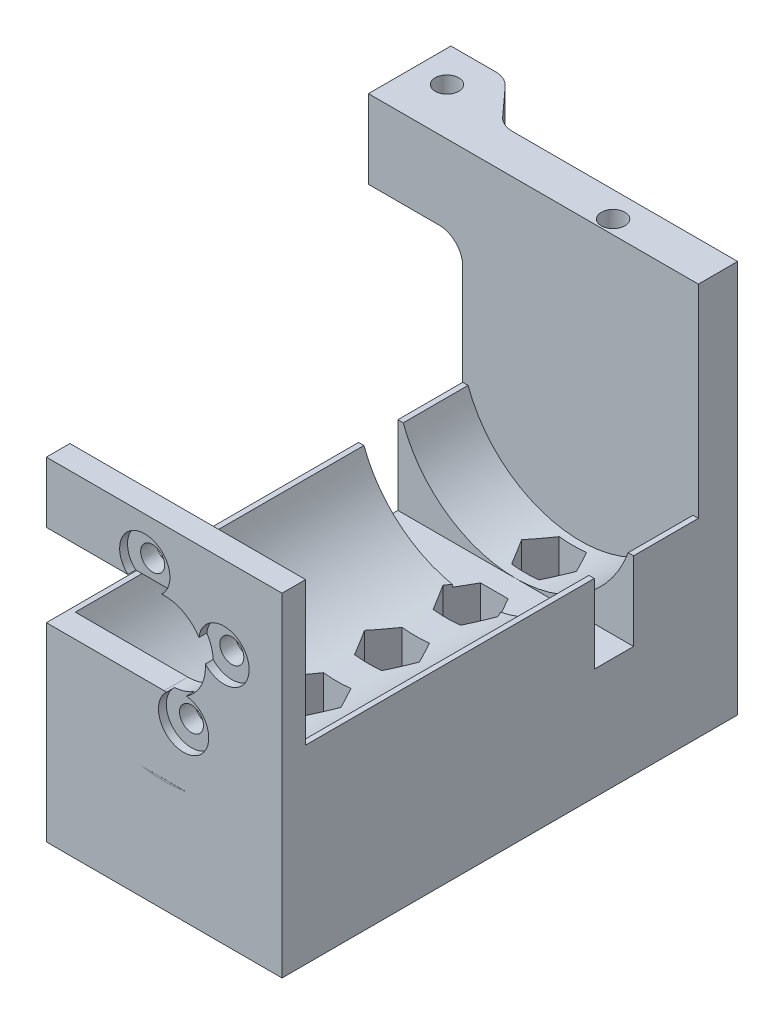
SolidWorks part; units mm, degrees
ref_plane "Front Plane" through (0, 0, 0) normal (0, 0, 1) x (1, 0, 0)
ref_plane "Top Plane" through (0, 0, 0) normal (0, 1, 0) x (1, 0, 0)
ref_plane "Right Plane" through (0, 0, 0) normal (1, 0, 0) x (0, 0, -1)
sketch "Sketch1" plane through (0, 0, 0) normal (0, 0, 1) x (1, 0, 0)
  line L1 (-15, -15) -> (15, -15)
  line L5 (-15, -15) -> (-15, -5.25)
  line L6 (15, -15) -> (15, 13)
  line L9 (-15, 13) -> (15, 13)
  line L11 (0, -5.25) -> (-15, -5.25)
  line L12 (0, 5.25) -> (-15, 5.25)
  line L13 (-15, 5.25) -> (-15, 13)
  line L14 (0, 0) -> (0, 8) construction
  line L15 (2.4721, -7.6085) -> (-2.4721, 7.6085) construction
  line L16 (0, 0) -> (7.6085, 2.4721) construction
  arc A0 (0, -5.25) -> (5.25, 0) centre (0, 0) ccw
  circle A1 centre (0, 0) radius 8 construction
  arc A5 (0, 5.25) -> (5.25, 0) centre (0, 0) cw
  circle A7 centre (-2.4721, 7.6085) radius 1.525
  circle A10 centre (7.6085, 2.4721) radius 1.525
  circle A11 centre (2.4721, -7.6085) radius 1.525
  dimension "D2" = 10.5
  dimension "D5" = 16
  dimension "D6" = 18
  dimension "D8" = 3.05
  dimension "D1" = 30
  dimension "D3" = 28
  dimension "D7" = 90
extrude "Boss-Extrude1" add sketch "Sketch1" along normal blind 3
sketch "Sketch2" plane through (0, 0, 3) normal (0, 0, 1) x (1, 0, 0)
  line L0 (-15, -15) -> (-15, -5.25)
  line L2 (-15, -15) -> (-15, -29.425)
  line L3 (-15, -29.425) -> (15, -29.425)
  line L4 (15, -15) -> (15, -29.425)
  line L6 (15, -15) -> (15, -5.25)
  line L8 (-15, -5.25) -> (-14.3178, -5.25)
  line L9 (0, -5.25) -> (-15, -5.25) construction
  line L10 (-14.3178, -5.25) -> (16.0436, -5.25) construction
  line L11 (15, -5.25) -> (14.3178, -5.25)
  arc A0 (-14.3178, -5.25) -> (14.3178, -5.25) centre (0, 0) ccw
  dimension "D2" = 30.5
  dimension "D4" = 15.25
  dimension "D1" = 14.425
  dimension "D3" = 14.425
extrude "Boss-Extrude2" add sketch "Sketch2" against normal blind 53
sketch "Sketch3" plane through (0, -29.425, 0) normal (0, -1, 0) x (-1, 0, 0)
  line L0 (0, -3) -> (0, 50) construction
  line L1 (15, -3) -> (-15, -3) construction
  line L2 (15, 50) -> (-15, 50) construction
  circle A0 centre (0, 46) radius 1.55
  circle A1 centre (0, 36) radius 1.55
  circle A2 centre (0, 26) radius 1.55
  circle A3 centre (0, 16) radius 1.55
  circle A4 centre (0, 6) radius 1.55
  dimension "D1" = 3.1
  dimension "D2" = 4
  dimension "D3" = 5
extrude "Cut-Extrude1" cut sketch "Sketch3" against normal through all
sketch "Sketch4" plane through (0, 0, 3) normal (0, 0, 1) x (1, 0, 0)
  line L0 (-2.75, -15) -> (2.694, -15.0102)
  arc A0 (-2.75, -15) -> (2.694, -15.0102) centre (0, 0) ccw
extrude "Boss-Extrude3" add sketch "Sketch4" against normal blind 3 separate body
sketch "Sketch5" plane through (0, -29.425, 0) normal (0, -1, 0) x (-1, 0, 0)
  line L0 (3.493, 36) -> (1.7465, 39.025)
  line L1 (3.493, 46) -> (1.7465, 49.025)
  line L2 (1.7465, 49.025) -> (-1.7465, 49.025)
  line L3 (-1.7465, 49.025) -> (-3.493, 46)
  line L4 (-3.493, 46) -> (-1.7465, 42.975)
  line L5 (-1.7465, 42.975) -> (1.7465, 42.975)
  line L6 (1.7465, 42.975) -> (3.493, 46)
  line L7 (1.7465, 39.025) -> (-1.7465, 39.025)
  line L8 (-1.7465, 39.025) -> (-3.493, 36)
  line L9 (-3.493, 36) -> (-1.7465, 32.975)
  line L10 (-1.7465, 32.975) -> (1.7465, 32.975)
  line L11 (1.7465, 32.975) -> (3.493, 36)
  line L12 (3.493, 26) -> (1.7465, 29.025)
  line L13 (1.7465, 29.025) -> (-1.7465, 29.025)
  line L14 (-1.7465, 29.025) -> (-3.493, 26)
  line L15 (-3.493, 26) -> (-1.7465, 22.975)
  line L16 (-1.7465, 22.975) -> (1.7465, 22.975)
  line L17 (1.7465, 22.975) -> (3.493, 26)
  line L18 (3.493, 16) -> (1.7465, 19.025)
  line L19 (1.7465, 19.025) -> (-1.7465, 19.025)
  line L20 (-1.7465, 19.025) -> (-3.493, 16)
  line L21 (-3.493, 16) -> (-1.7465, 12.975)
  line L22 (-1.7465, 12.975) -> (1.7465, 12.975)
  line L23 (1.7465, 12.975) -> (3.493, 16)
  line L24 (3.493, 6) -> (1.7465, 9.025)
  line L25 (1.7465, 9.025) -> (-1.7465, 9.025)
  line L26 (-1.7465, 9.025) -> (-3.493, 6)
  line L27 (-3.493, 6) -> (-1.7465, 2.975)
  line L28 (-1.7465, 2.975) -> (1.7465, 2.975)
  line L29 (1.7465, 2.975) -> (3.493, 6)
  circle A5 centre (0, 46) radius 3.025 construction
  circle A6 centre (0, 36) radius 3.025 construction
  circle A7 centre (0, 26) radius 3.025 construction
  circle A8 centre (0, 16) radius 3.025 construction
  circle A9 centre (0, 6) radius 3.025 construction
  dimension "D1" = 6.05
  dimension "D2" = 5
extrude "Cut-Extrude2" cut sketch "Sketch5" against normal through all from offset 5 offset against normal yes
sketch "Sketch6" plane through (0, 0, 3) normal (0, 0, 1) x (1, 0, 0)
  circle A1 centre (2.4721, -7.6085) radius 3.2
  circle A4 centre (-2.4721, 7.6085) radius 3.2
  circle A5 centre (7.6085, 2.4721) radius 3.2
  dimension "D1" = 6.4
extrude "Cut-Extrude3" cut sketch "Sketch6" against normal blind 1
sketch "Sketch7" plane through (0, 0, -50) normal (0, 0, -1) x (-1, 0, 0)
  line L0 (15, 13) -> (15, 2.75) construction
  line L1 (-15, -29.425) -> (15, -29.425)
  line L2 (-15, -29.425) -> (-15, 20.575)
  line L3 (-15, 20.575) -> (15, 20.575)
  line L4 (15, -29.425) -> (15, 20.575)
  dimension "D1" = 50
extrude "Boss-Extrude4" add sketch "Sketch7" along normal blind 5
sketch "Sketch9" plane through (-15, 0, 0) normal (-1, 0, 0) x (0, 0, 1)
  line L5 (3, -5.25) -> (-50, -5.25) construction
  line L6 (-41.75, -15.25) -> (-36.75, -15.25)
  line L9 (-41.75, -15.25) -> (-41.75, 4.75)
  line L10 (-41.75, 4.75) -> (-36.75, 4.75)
  line L11 (-36.75, -15.25) -> (-36.75, 4.75)
  line L12 (-41.75, -15.25) -> (-36.75, 4.75) construction
  line L13 (-41.75, 4.75) -> (-36.75, -15.25) construction
  line L14 (3, -5.25) -> (3, -29.425) construction
  point P0 (-39.25, -5.25)
  dimension "D1" = 42.25
  dimension "D2" = 5
  dimension "D3" = 20
extrude "Cut-Extrude6" cut sketch "Sketch9" against normal through all
sketch "Sketch10" plane through (0, -29.425, 0) normal (0, -1, 0) x (-1, 0, 0)
  line L0 (15, 26) -> (-15, 26) construction
  line L1 (15, 55) -> (15, -3) construction
  line L2 (-15, 55) -> (-15, -3) construction
  circle A0 centre (5, 26) radius 6.55
  dimension "D1" = 13.1
  dimension "D2" = 10
extrude "Cut-Extrude7" cut sketch "Sketch10" against normal blind 2
sketch "Sketch11" plane through (0, 20.575, 0) normal (0, 1, 0) x (1, 0, 0)
  line L0 (-15, 50) -> (-27, 50)
  line L1 (-27, 50) -> (-27, 60.5)
  line L2 (-27, 60.5) -> (-20, 60.5)
  line L4 (-15, 55) -> (15, 55) construction
  line L6 (-15, 55) -> (-15, 50)
  line L9 (-20, 60.5) -> (-15, 55)
  circle A0 centre (-23, 56) radius 1.5
  dimension "D4" = 3
  dimension "D5" = 4.5
  dimension "D1" = 5.5
  dimension "D2" = 12
  dimension "D3" = 7
  dimension "D6" = 4
extrude "Boss-Extrude5" add sketch "Sketch11" against normal blind 10 contours L2 L9 L6 L0 L1 | A0
sketch "Sketch12" plane through (0, 20.575, 0) normal (0, 1, 0) x (1, 0, 0)
  line L0 (-15, 41.75) -> (-15, 50) construction
  line L2 (-15, 55) -> (15, 55) construction
  circle A0 centre (2.4, 51.75) radius 1.5
  dimension "D3" = 3
  dimension "D1" = 17.4
  dimension "D2" = 3.25
extrude "Cut-Extrude8" cut sketch "Sketch12" against normal blind 10
fillet "Fillet1" radius 3 2 edges at (-20, 15.575, -60.5) (-15, 15.575, -55)
fillet "Fillet2" radius 3 1 edges at (-15, 10.575, -52.5)
